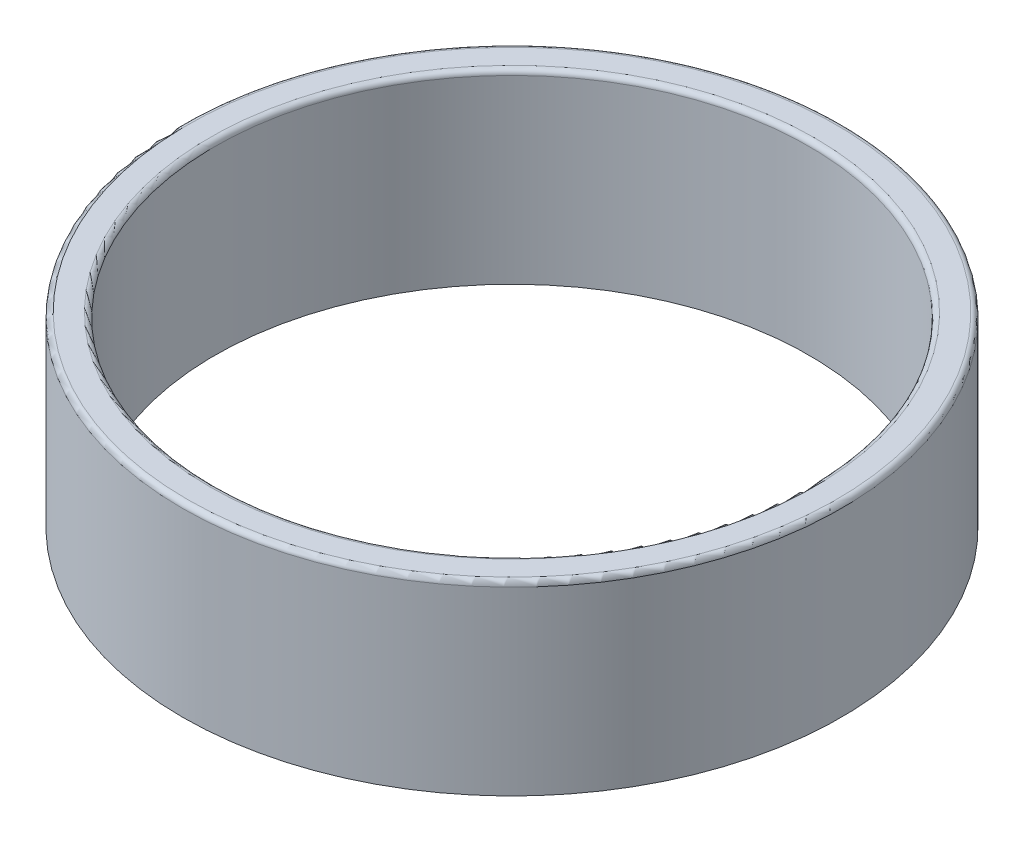
SolidWorks part; units mm, degrees
ref_plane "Front Plane" through (0, 0, 0) normal (0, 0, 1) x (1, 0, 0)
ref_plane "Top Plane" through (0, 0, 0) normal (0, 1, 0) x (1, 0, 0)
ref_plane "Right Plane" through (0, 0, 0) normal (1, 0, 0) x (0, 0, -1)
sketch "Sketch1" plane through (0, 0, 0) normal (0, 1, 0) x (1, 0, 0)
  circle A0 centre (0, 0) radius 40.9194
  circle A1 centre (0, 0) radius 36.9062
  dimension "D1" = 81.8388
  dimension "D2" = 4.0132
extrude "Boss-Extrude1" add sketch "Sketch1" along normal blind 23.0886
fillet "Fillet1" radius 0.635 2 edges at (0, 23.0886, 36.9062) (0, 23.0886, 40.9194)
sketch "Sketch2" plane through (0, 0, 0) normal (0, 0, 1) x (1, 0, 0)
  line L0 (42.9514, 21.157) -> (42.9514, 16.9638)
  line L1 (40.9194, 0) -> (40.9194, 22.4536) construction
  line L2 (40.2844, 23.0886) -> (-40.2844, 23.0886) construction
  line L3 (40.9194, 20.9296) -> (40.9194, 17.1217)
  arc A0 (40.9194, 20.9296) -> (41.4604, 20.4227) centre (41.4274, 20.9296) ccw
  arc A1 (41.4604, 20.4227) -> (41.4604, 17.6287) centre (41.5514, 19.0257) cw
  arc A2 (41.4604, 17.6287) -> (40.9194, 17.1217) centre (41.4274, 17.1217) ccw
  dimension "D3" = 0.508
  dimension "D4" = 0.508
  dimension "D1" = 2.159
  dimension "D2" = 2.794
  dimension "D5" = 2.032
ref_plane "Plane1" through (0, 19.0257, 0) normal (0, 1, 0) x (1, 0, 0)
ref_plane "Plane2" through (0, 12.6757, 0) normal (0, 1, 0) x (1, 0, 0)
ref_plane "Plane3" through (0, 15.8507, 0) normal (0, 1, 0) x (1, 0, 0)
sketch "Sketch4" plane through (0, 15.8507, 0) normal (0, 1, 0) x (1, 0, 0)
  point P0 (0, 0)
sketch3d "3DSketch2"
  arc A0 (41.5514, 19.0257, 0) -> (39.7606, 12.3614, -11.9802) centre (0, 15.8507, 0) cw
  point P2 (2.7899, -20.6607, 19.8932)
